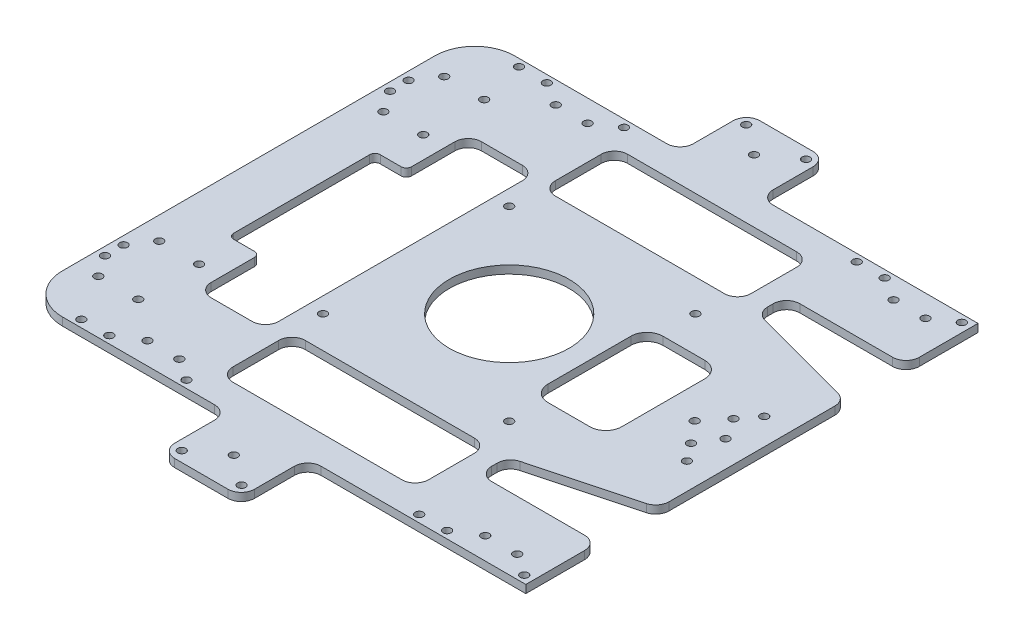
SolidWorks part; units mm, degrees
ref_plane "前视基准面" through (0, 0, 0) normal (0, 0, 1) x (1, 0, 0)
ref_plane "上视基准面" through (0, 0, 0) normal (0, 1, 0) x (1, 0, 0)
ref_plane "右视基准面" through (0, 0, 0) normal (1, 0, 0) x (0, 0, -1)
other "Configuration Table"
sketch "草图1" plane through (0, 0, 0) normal (0, 1, 0) x (1, 0, 0)
  line L0 (-91.25, 85) -> (-97.9595, 85)
  line L1 (-91.25, 85) -> (-35.75, 85)
  line L3 (-91.25, -85) -> (-35.75, -85)
  line L4 (91.25, 85) -> (91.25, 57.9182)
  line L5 (-91.25, 85) -> (91.25, -85) construction
  line L6 (-91.25, -85) -> (91.25, 85) construction
  line L7 (44.25, -85) -> (91.25, -85)
  line L8 (-97.9595, 85) -> (-97.9595, -85)
  line L9 (-82.75, -85) -> (-92.6165, -85) construction
  line L10 (-97.9595, -85) -> (-91.25, -85)
  line L11 (-89.4436, 33.7248) -> (-89.4436, 26.7248) construction
  line L13 (-74.4436, -42.1331) -> (-89.4436, -42.1331) construction
  line L14 (-89.4436, 85) -> (-89.4436, -85) construction
  line L15 (0, 0) -> (-228.1626, 0) construction
  line L23 (44.25, 85) -> (91.25, 85)
  line L24 (91.25, -57.9182) -> (91.25, -85)
  line L25 (46.356, 57.9182) -> (91.25, 57.9182)
  line L26 (46.356, 57.9182) -> (46.356, 47.0062)
  line L27 (46.356, -57.9182) -> (91.25, -57.9182)
  line L29 (-40.8461, 50.8132) -> (-66.2289, 50.8132)
  line L30 (-40.8461, 50.8132) -> (-40.8461, -50.8132)
  line L31 (-40.8461, -50.8132) -> (-66.2289, -50.8132)
  line L32 (-66.2289, 50.8132) -> (-66.2289, -50.8132)
  line L33 (0, 0) -> (0, -26.7248) construction
  line L34 (-35, 35) -> (35, 35) construction
  line L35 (-35, 35) -> (-35, -35) construction
  line L36 (-35, -35) -> (35, -35) construction
  line L37 (35, 35) -> (35, -35) construction
  line L38 (-35, 35) -> (35, -35) construction
  line L39 (-35, -35) -> (35, 35) construction
  line L40 (-35.75, -85) -> (-25.75, -85)
  line L41 (47.4478, 0) -> (171.4759, 0) construction
  line L42 (-20.75, -90) -> (-20.75, -104.9826)
  line L43 (-15.75, -109.9826) -> (4.25, -109.9826)
  line L44 (9.25, -104.9826) -> (9.25, -90)
  line L45 (14.25, -85) -> (44.25, -85)
  line L46 (14.25, 85) -> (44.25, 85)
  line L47 (9.25, 104.9826) -> (9.25, 90)
  line L48 (-15.75, 109.9826) -> (4.25, 109.9826)
  line L49 (-20.75, 90) -> (-20.75, 104.9826)
  line L50 (-35.75, 85) -> (-25.75, 85)
  line L51 (-34.6402, -47.0062) -> (38.8805, -47.0062)
  line L52 (-34.6402, 74.2132) -> (38.8805, 74.2132)
  line L53 (-34.6402, 74.2132) -> (-34.6402, 47.0062)
  line L54 (-34.6402, 47.0062) -> (38.8805, 47.0062)
  line L55 (38.8805, 74.2132) -> (38.8805, 47.0062)
  line L56 (38.8805, -74.2132) -> (38.8805, -47.0062)
  line L57 (-34.6402, -74.2132) -> (38.8805, -74.2132)
  line L58 (-34.6402, -74.2132) -> (-34.6402, -47.0062)
  line L59 (46.356, 47.0062) -> (91.25, 35)
  line L60 (91.25, 35) -> (91.25, -35)
  line L61 (91.25, -35) -> (46.356, -47.0062)
  line L62 (46.356, -47.0062) -> (46.356, -57.9182)
  line L63 (-89.4436, 65.0248) -> (-74.4436, 65.0248) construction
  line L64 (57.9405, 21.6087) -> (30.1732, 21.6087)
  line L65 (57.9405, 21.6087) -> (57.9405, -21.6087)
  line L66 (57.9405, -21.6087) -> (30.1732, -21.6087)
  line L67 (30.1732, 21.6087) -> (30.1732, -21.6087)
  line L68 (-74.4436, 65.0248) -> (-74.4436, 42.1331) construction
  line L69 (-74.4436, 42.1331) -> (-89.4436, 42.1331) construction
  line L70 (-89.4436, 42.1331) -> (-89.4436, 65.0248) construction
  line L71 (-89.4436, -42.1331) -> (-89.4436, -65.0248) construction
  line L72 (-74.4436, -65.0248) -> (-74.4436, -42.1331) construction
  line L73 (-89.4436, -65.0248) -> (-74.4436, -65.0248) construction
  circle A5 centre (-89.4436, 65.0248) radius 1.5
  circle A6 centre (-74.4436, 65.0248) radius 1.5
  circle A9 centre (-78.5908, -82.25) radius 1.5
  circle A10 centre (-68.0908, -82.25) radius 1.5
  circle A11 centre (-39.0908, -82.25) radius 1.5
  circle A12 centre (48.4092, -82.25) radius 1.5
  circle A13 centre (58.9092, -82.25) radius 1.5
  circle A14 centre (87.9092, -82.25) radius 1.5
  circle A15 centre (-78.5908, 82.25) radius 1.5
  circle A16 centre (-68.0908, 82.25) radius 1.5
  circle A17 centre (-39.0908, 82.25) radius 1.5
  circle A18 centre (48.4092, 82.25) radius 1.5
  circle A19 centre (58.9092, 82.25) radius 1.5
  circle A20 centre (87.9092, 82.25) radius 1.5
  circle A21 centre (-59.25, 76.75) radius 1.5
  circle A22 centre (-47.25, 76.75) radius 1.5
  circle A23 centre (-59.25, -76.75) radius 1.5
  circle A24 centre (-47.25, -76.75) radius 1.5
  circle A25 centre (67.75, 76.75) radius 1.5
  circle A26 centre (79.75, 76.75) radius 1.5
  circle A27 centre (67.75, -76.75) radius 1.5
  circle A28 centre (79.75, -76.75) radius 1.5
  circle A29 centre (-89.4436, 42.1331) radius 1.5
  circle A30 centre (-74.4436, 42.1331) radius 1.5
  circle A35 centre (-35, 35) radius 1.5
  circle A36 centre (-35, -35) radius 1.5
  circle A37 centre (35, -35) radius 1.5
  circle A38 centre (35, 35) radius 1.5
  arc A39 (-25.75, -85) -> (-20.75, -90) centre (-25.75, -90) cw
  arc A40 (4.25, -109.9826) -> (9.25, -104.9826) centre (4.25, -104.9826) ccw
  arc A41 (-20.75, -104.9826) -> (-15.75, -109.9826) centre (-15.75, -104.9826) ccw
  arc A42 (9.25, -90) -> (14.25, -85) centre (14.25, -90) cw
  circle A43 centre (-5.75, -97.7894) radius 1.5
  circle A44 centre (-17, -106.1) radius 1.5
  circle A45 centre (5.5, -106.1) radius 1.5
  circle A46 centre (5.5, 106.1) radius 1.5
  circle A47 centre (-17, 106.1) radius 1.5
  circle A48 centre (-5.75, 97.7894) radius 1.5
  arc A49 (9.25, 90) -> (14.25, 85) centre (14.25, 90) ccw
  arc A50 (-20.75, 104.9826) -> (-15.75, 109.9826) centre (-15.75, 104.9826) cw
  arc A51 (4.25, 109.9826) -> (9.25, 104.9826) centre (4.25, 104.9826) cw
  arc A52 (-25.75, 85) -> (-20.75, 90) centre (-25.75, 90) ccw
  circle A53 centre (0, 0) radius 22.5
  circle A54 centre (-74.4436, -42.1331) radius 1.5
  circle A55 centre (-89.4436, -42.1331) radius 1.5
  circle A56 centre (-74.4436, -65.0248) radius 1.5
  circle A57 centre (-89.4436, -65.0248) radius 1.5
  point P0 (0, 0)
  point P133 (-20.75, -85)
  point P139 (9.25, -85)
  point P167 (9.25, 85)
  point P168 (-20.75, 85)
  dimension "D3" = 70
  dimension "D4" = 70
  dimension "D5" = 3
  dimension "D7" = 3
  dimension "D8" = 3
  dimension "D10" = 5
  dimension "D11" = 5
  dimension "D1" = 170
  dimension "D2" = 182.5
  dimension "D6" = 7
  dimension "D9" = 15
  dimension "D12" = 22.8917
extrude "凸台-拉伸1" add sketch "草图1" along normal blind 3
fillet "圆角2" radius 15 1 edges at (-97.9595, 1.5, -85)
fillet "圆角3" radius 15 1 edges at (-97.9595, 1.5, 85)
sketch "草图2" plane through (0, 3, 0) normal (0, 1, 0) x (1, 0, 0)
  circle A0 centre (-94.8899, 57.079) radius 1.5
  circle A1 centre (-94.8899, 50.079) radius 1.5
  circle A2 centre (-94.8899, -50.079) radius 1.5
  circle A3 centre (-94.8899, -57.079) radius 1.5
extrude "切除-拉伸1" cut sketch "草图2" against normal through all
fillet "圆角6" radius 5 12 edges at (-40.8461, 1.5, 50.8132) (-66.2289, 1.5, 50.8132) (-66.2289, 1.5, -50.8132) (-40.8461, 1.5, -50.8132) (46.356, 1.5, -57.9182) (91.25, 1.5, -57.9182) (91.25, 1.5, 57.9182) (91.25, 1.5, -35) (91.25, 1.5, 35) (46.356, 1.5, -47.0062) (46.356, 1.5, 47.0062) (46.356, 1.5, 57.9182)
fillet "圆角7" radius 5 8 edges at (-34.6402, 1.5, -47.0062) (38.8805, 1.5, -47.0062) (38.8805, 1.5, -74.2132) (-34.6402, 1.5, -74.2132) (38.8805, 1.5, 74.2132) (-34.6402, 1.5, 74.2132) (38.8805, 1.5, 47.0062) (-34.6402, 1.5, 47.0062)
sketch "草图3" plane through (0, 3, 0) normal (0, 1, 0) x (1, 0, 0)
  line L0 (91.25, 0) -> (-155.3356, 0) construction
  line L1 (91.25, -31.1615) -> (91.25, 31.1615) construction
  circle A0 centre (81.3625, 14.5262) radius 1.5
  circle A1 centre (81.3625, -14.5262) radius 1.5
  circle A2 centre (76.3421, -7.9763) radius 1.5
  circle A3 centre (76.3421, 7.9763) radius 1.5
  circle A4 centre (81.3625, 0) radius 1.5
  circle A5 centre (69.7317, 0) radius 1.5
  dimension "D1" = 3
  dimension "D2" = 3
  dimension "D3" = 3
  dimension "D4" = 3
extrude "切除-拉伸2" cut sketch "草图3" against normal up to next
fillet "圆角8" radius 6 4 edges at (30.1732, 1.5, 21.6087) (57.9405, 1.5, 21.6087) (57.9405, 1.5, -21.6087) (30.1732, 1.5, -21.6087)
sketch "草图4" plane through (0, 3, 0) normal (0, 1, 0) x (1, 0, 0)
  line L0 (91.25, 0) -> (-164.2506, 0) construction
  line L1 (-78.0216, -27.5566) -> (-62.1048, -27.5566)
  line L2 (-78.0216, -27.5566) -> (-78.0216, 27.5566)
  line L3 (-78.0216, 27.5566) -> (-62.1048, 27.5566)
  line L4 (-62.1048, -27.5566) -> (-62.1048, 27.5566)
  line L5 (91.25, -31.1615) -> (91.25, 31.1615) construction
extrude "切除-拉伸3" cut sketch "草图4" against normal through all
fillet "圆角9" radius 2 2 edges at (-78.0216, 1.5, -27.5566) (-78.0216, 1.5, 27.5566)
fillet "圆角10" radius 2 2 edges at (-66.2289, 1.5, 27.5566) (-66.2289, 1.5, -27.5566)
